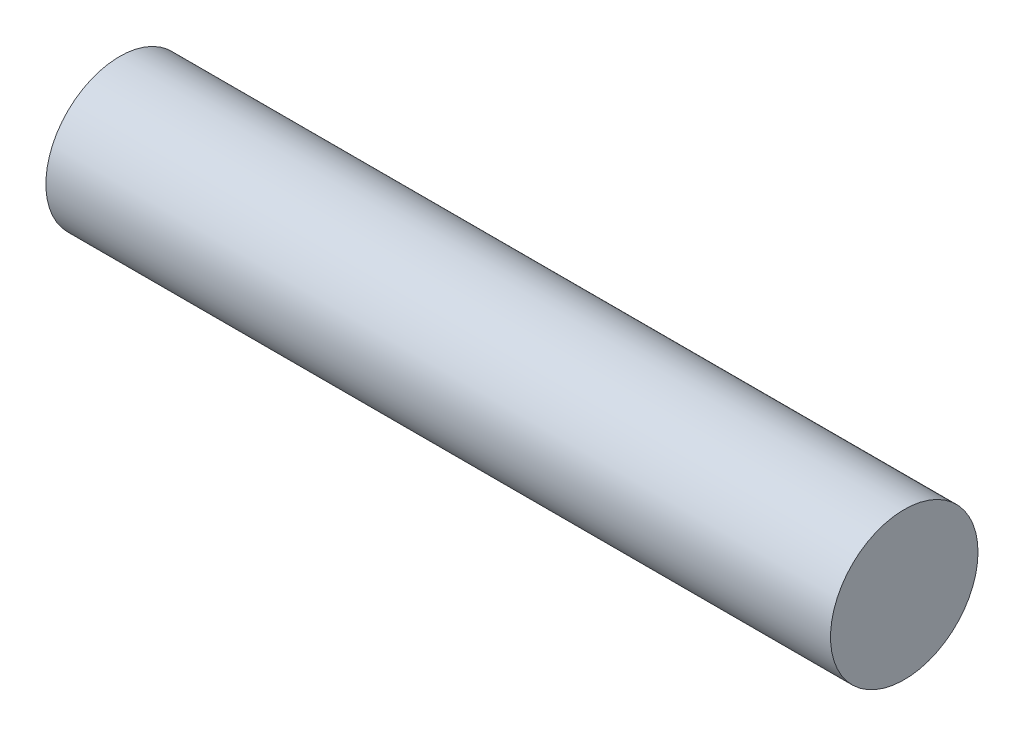
SolidWorks part; units mm, degrees
ref_plane "Front Plane" through (0, 0, 0) normal (0, 0, 1) x (1, 0, 0)
ref_plane "Top Plane" through (0, 0, 0) normal (0, 1, 0) x (1, 0, 0)
ref_plane "Right Plane" through (0, 0, 0) normal (1, 0, 0) x (0, 0, -1)
sketch "Sketch1" plane through (0, 0, 0) normal (1, 0, 0) x (0, 0, -1)
  circle A0 centre (0, 0) radius 2.5
  dimension "D1" = 5
extrude "Boss-Extrude1" add sketch "Sketch1" along normal blind 26.6
